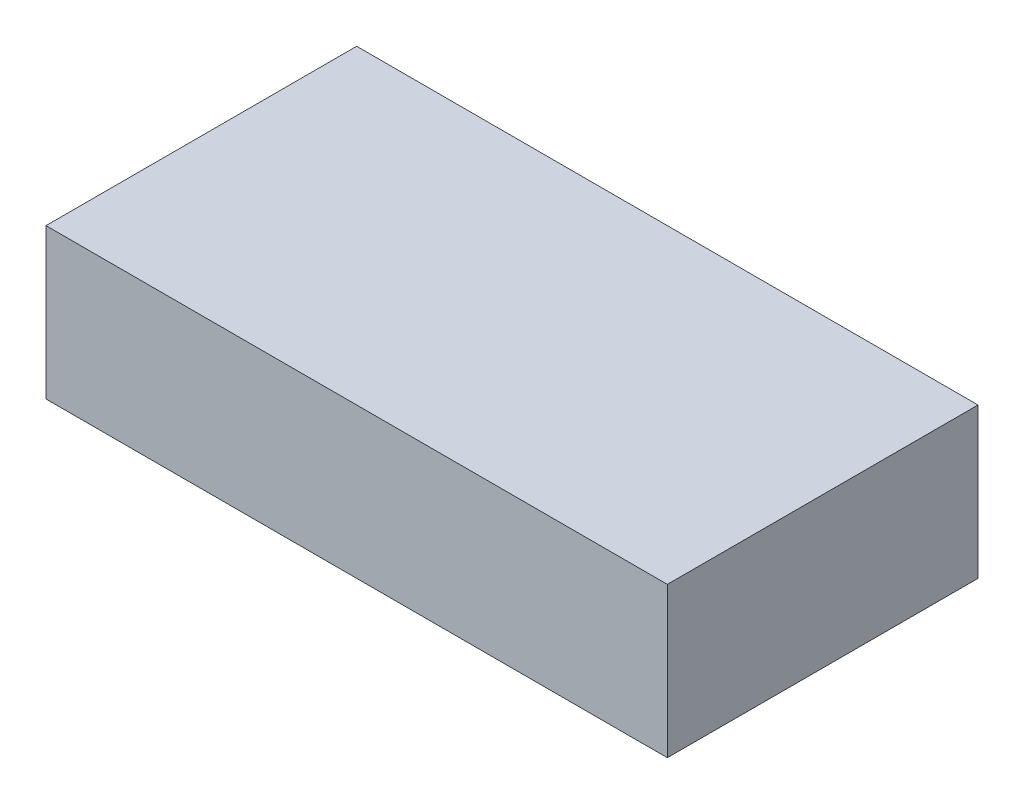
SolidWorks part; units mm, degrees
ref_plane "前视基准面" through (0, 0, 0) normal (0, 0, 1) x (1, 0, 0)
ref_plane "上视基准面" through (0, 0, 0) normal (0, 1, 0) x (1, 0, 0)
ref_plane "右视基准面" through (0, 0, 0) normal (1, 0, 0) x (0, 0, -1)
sketch "草图1" plane through (0, 0, 0) normal (0, 1, 0) x (1, 0, 0)
  line L1 (0, 0) -> (60, 0)
  line L2 (0, 0) -> (0, 30)
  line L3 (0, 30) -> (60, 30)
  line L4 (60, 0) -> (60, 30)
  dimension "D1" = 60
  dimension "D2" = 30
extrude "凸台-拉伸1" add sketch "草图1" along normal blind 14.5
